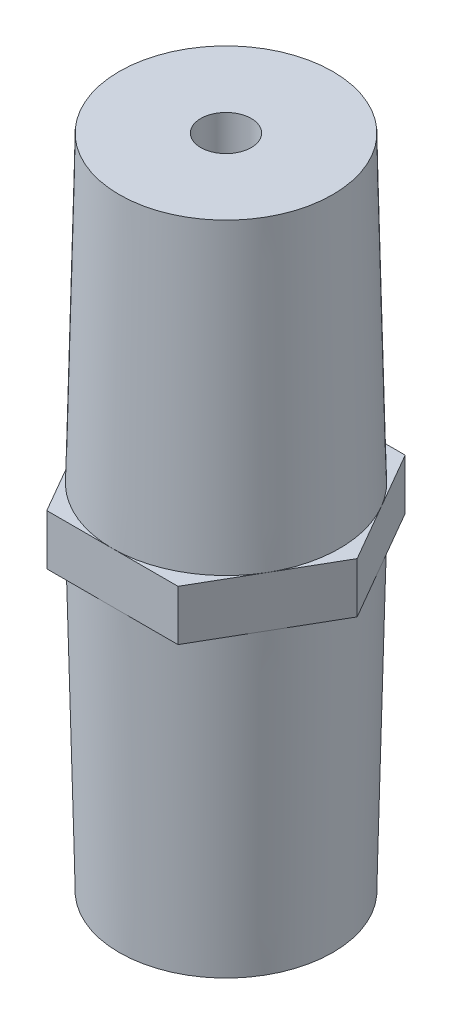
SolidWorks part; units mm, degrees
material "6061-T6 (SS)"
ref_plane "Front Plane" through (0, 0, 0) normal (0, 0, 1) x (1, 0, 0)
ref_plane "Top Plane" through (0, 0, 0) normal (0, 1, 0) x (1, 0, 0)
ref_plane "Right Plane" through (0, 0, 0) normal (1, 0, 0) x (0, 0, -1)
sketch "Sketch3" plane through (0, 0, 0) normal (0, 1, 0) x (1, 0, 0)
  line L1 (8.2489, 0) -> (4.1244, 7.1437)
  line L2 (4.1244, 7.1437) -> (-4.1244, 7.1437)
  line L3 (-4.1244, 7.1437) -> (-8.2489, 0)
  line L4 (-8.2489, 0) -> (-4.1244, -7.1437)
  line L5 (-4.1244, -7.1437) -> (4.1244, -7.1437)
  line L6 (4.1244, -7.1437) -> (8.2489, 0)
  circle A0 centre (0, 0) radius 7.1437 construction
  dimension "D1" = 14.2875
extrude "Boss-Extrude3" add sketch "Sketch3" along normal blind 1.5875
sketch "Sketch4" plane through (0, 1.5875, 0) normal (0, 1, 0) x (1, 0, 0)
  line L0 (-4.1244, 7.1437) -> (-8.2489, 0) construction
  circle A0 centre (0, 0) radius 7.1438
extrude "Boss-Extrude4" add sketch "Sketch4" along normal blind 19.05 draft 1.3
mirror "Mirror1" about plane through (0, 0, 0) normal (0, 1, 0) of "Boss-Extrude3", "Boss-Extrude4"
sketch "Sketch5" plane through (0, 20.6375, 0) normal (0, 1, 0) x (1, 0, 0)
  circle A0 centre (0, 0) radius 1.5875
  dimension "D1" = 3.175
extrude "Cut-Extrude1" cut sketch "Sketch5" against normal through all
